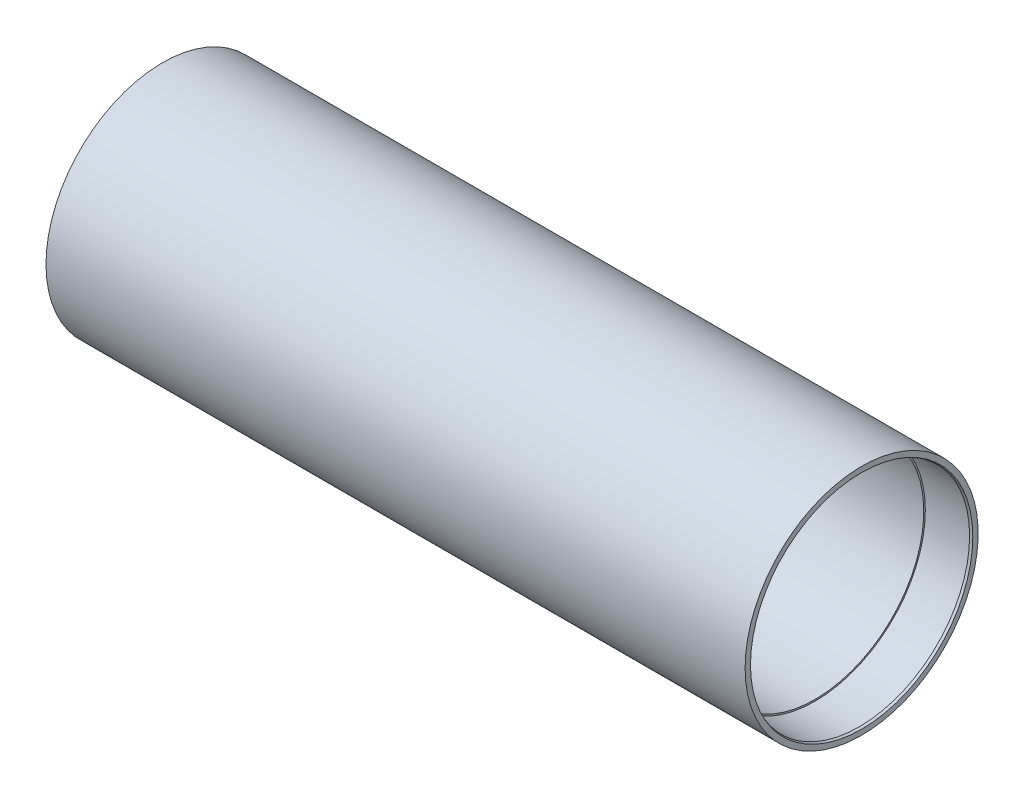
SolidWorks part; units mm, degrees
material "6063-T5"
ref_plane "正面" through (0, 0, 0) normal (0, 0, 1) x (1, 0, 0)
ref_plane "平面" through (0, 0, 0) normal (0, 1, 0) x (1, 0, 0)
ref_plane "右側面" through (0, 0, 0) normal (1, 0, 0) x (0, 0, -1)
sketch "ｽｹｯﾁ1" plane through (0, 0, 0) normal (0, 0, 1) x (1, 0, 0)
  line L0 (0, 0) -> (235, 0) construction
  line L1 (-225, 70) -> (225, 70)
  line L2 (225, 70) -> (225, 75)
  line L3 (225, 75) -> (-225, 75)
  line L4 (-225, 75) -> (-225, 70)
  dimension "D1" = 225
  dimension "D2" = 225
  dimension "D3" = 70
  dimension "D4" = 75
revolve "素材 パイプ切断・端面仕上げ" add sketch "ｽｹｯﾁ1" angle 360 about L0
sketch "ｽｹｯﾁ2" plane through (0, 0, 0) normal (0, 0, 1) x (1, 0, 0)
  line L0 (0, 0) -> (235, 0) construction
  line L1 (195, 70) -> (195, 71)
  line L2 (195, 71) -> (223.5, 71)
  line L3 (223.5, 71) -> (225, 71.55)
  line L4 (225, 71.55) -> (225, 70)
  line L5 (225, 70) -> (195, 70)
  dimension "D2" = 225
  dimension "D1" = 195
  dimension "D3" = 223.5
  dimension "D4" = 71
  dimension "D5" = 70
  dimension "D6" = 71.55
revolve "シール面 内径仕上げ(前)" cut sketch "ｽｹｯﾁ2" angle 360 about L0
mirror "シール面 内径仕上げ(後)" about plane through (0, 0, 0) normal (1, 0, 0) of "シール面 内径仕上げ(前)"
equation "\"HULL_LEN\" = 450"
equation "\"D1@ｽｹｯﾁ1\" = \"HULL_LEN\" / 2"
equation "\"D2@ｽｹｯﾁ1\" = \"HULL_LEN\" / 2"
equation "\"HULL_ID\" = 140"
equation "\"D3@ｽｹｯﾁ1\" = \"HULL_ID\" / 2"
equation "\"HULL_OD\" = 150"
equation "\"D4@ｽｹｯﾁ1\" = \"HULL_OD\" / 2"
equation "\"SEAL_LEN\" = 30"
equation "\"D1@ｽｹｯﾁ2\" = \"HULL_LEN\" / 2 - \"SEAL_LEN\""
equation "\"D2@ｽｹｯﾁ2\" = \"HULL_LEN\" / 2"
equation "\"LEAD_AX\" = 1.5"
equation "\"D3@ｽｹｯﾁ2\" = \"HULL_LEN\" / 2 - \"LEAD_AX\""
equation "\"SEAL_BORE\" = 142"
equation "\"D4@ｽｹｯﾁ2\" = \"SEAL_BORE\" / 2"
equation "\"D5@ｽｹｯﾁ2\" = \"HULL_ID\" / 2"
equation "\"LEAD_RAD\" = 0.55"
equation "\"D6@ｽｹｯﾁ2\" = \"SEAL_BORE\" / 2 + \"LEAD_RAD\""
